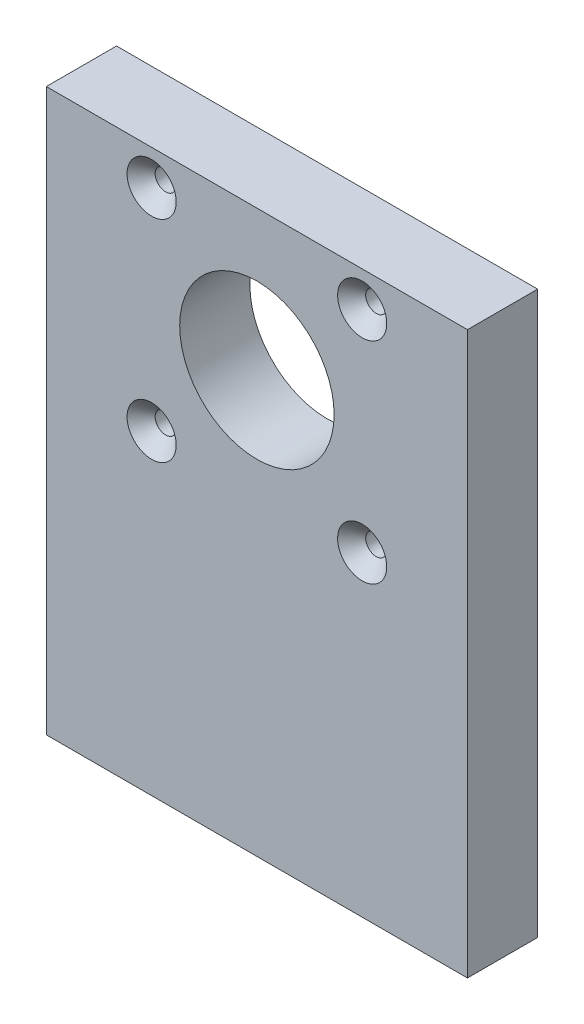
SolidWorks part; units mm, degrees
ref_plane "Front Plane" through (0, 0, 0) normal (0, 0, 1) x (1, 0, 0)
ref_plane "Top Plane" through (0, 0, 0) normal (0, 1, 0) x (1, 0, 0)
ref_plane "Right Plane" through (0, 0, 0) normal (1, 0, 0) x (0, 0, -1)
sketch "Sketch1" plane through (0, 0, 0) normal (0, 0, 1) x (1, 0, 0)
  line L1 (0, 0) -> (60, 0)
  line L2 (0, 0) -> (0, 80)
  line L3 (0, 80) -> (60, 80)
  line L4 (60, 0) -> (60, 80)
  circle A0 centre (30, 60) radius 11
  circle A1 centre (15, 75) radius 1.5
  circle A2 centre (45, 75) radius 1.5
  circle A3 centre (45, 45) radius 1.5
  circle A4 centre (15, 45) radius 1.5
extrude "Boss-Extrude1" add sketch "Sketch1" along normal blind 10
hole_wizard "M4x0.7 Tapped Hole1" positions "Sketch4" profile "Sketch3" tap size "M4x0.7" standard "ANSI Metric"
sketch "Sketch4" plane through (0, 0, 0) normal (0, -1, 0) x (-1, 0, 0)
  point P0 (-8, -5)
  point P2 (-30, -5)
  point P4 (-52, -5)
sketch "Sketch3" plane through (8, 0, 5) normal (1, 0, 0) x (0, 0, -1)
  line L0 (0, 0) -> (0, 11.0914)
  line L1 (0, 11.0914) -> (1.65, 10.1)
  line L2 (1.65, 10.1) -> (1.65, 0)
  line L5 (1.65, 0) -> (0, 0)
  line L10 (0, 11.0914) -> (-1.65, 10.1) construction
  line L11 (0, -6.35) -> (0, 107.95) construction
  dimension "Tap Drill Dia." = 3.3
  dimension "Tap Drill Depth" = 10.1
  dimension "Drill Angle" = 118
chamfer "Chamfer1" distance 2 angle 45 4 edges at (46.5, 45, 10) (16.5, 45, 10) (46.5, 75, 10) (16.5, 75, 10)
